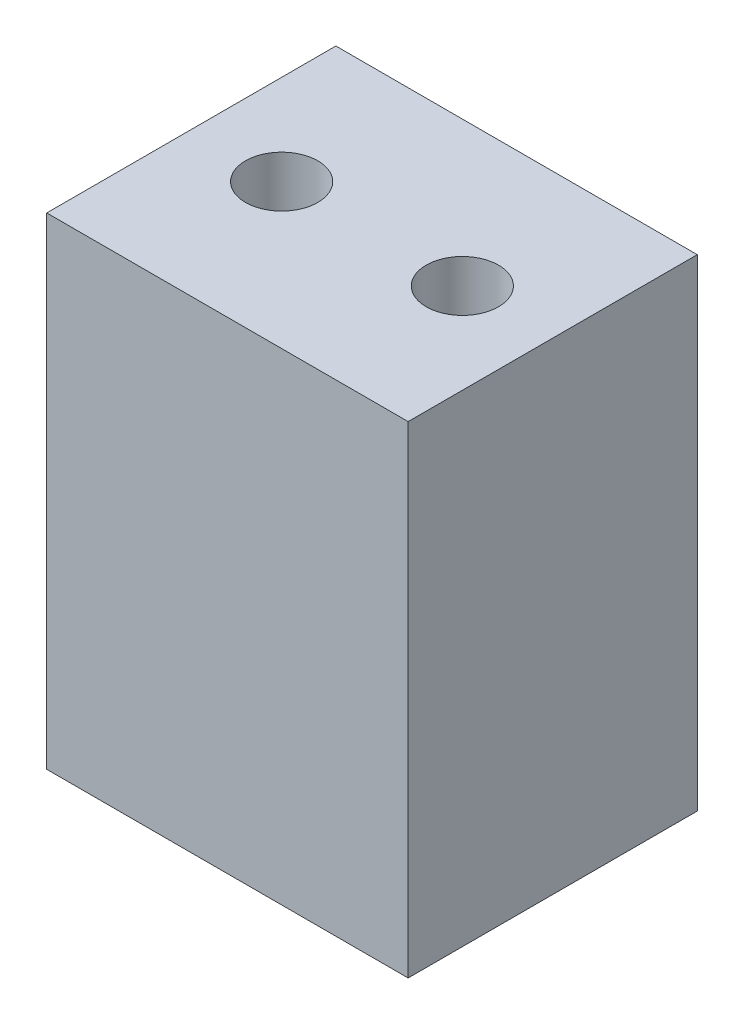
SolidWorks part; units mm, degrees
ref_plane "Front" through (0, 0, 0) normal (0, 0, 1) x (1, 0, 0)
ref_plane "Top" through (0, 0, 0) normal (0, 1, 0) x (1, 0, 0)
ref_plane "Right" through (0, 0, 0) normal (1, 0, 0) x (0, 0, -1)
sketch "Sketch1" plane through (0, 0, 0) normal (0, 1, 0) x (1, 0, 0)
  line L1 (0, 0) -> (30, 0)
  line L2 (0, 0) -> (0, 24)
  line L3 (0, 24) -> (30, 24)
  line L4 (30, 0) -> (30, 24)
  dimension "D1" = 24
  dimension "D2" = 30
extrude "Boss-Extrude1" add sketch "Sketch1" along normal blind 40
sketch "Sketch2" plane through (0, 40, 0) normal (0, 1, 0) x (1, 0, 0)
  line L0 (0, 24) -> (0, 0) construction
  line L2 (30, 0) -> (30, 24) construction
  circle A0 centre (7.5, 12) radius 3
  circle A1 centre (22.5, 12) radius 3
  point P6 (0, 12)
  point P7 (0, 0)
  dimension "D2" = 6
  dimension "D3" = 6
  dimension "D1" = 0
  dimension "D4" = 7.5
  dimension "D5" = 7.5
extrude "Cut-Extrude1" cut sketch "Sketch2" against normal through all
